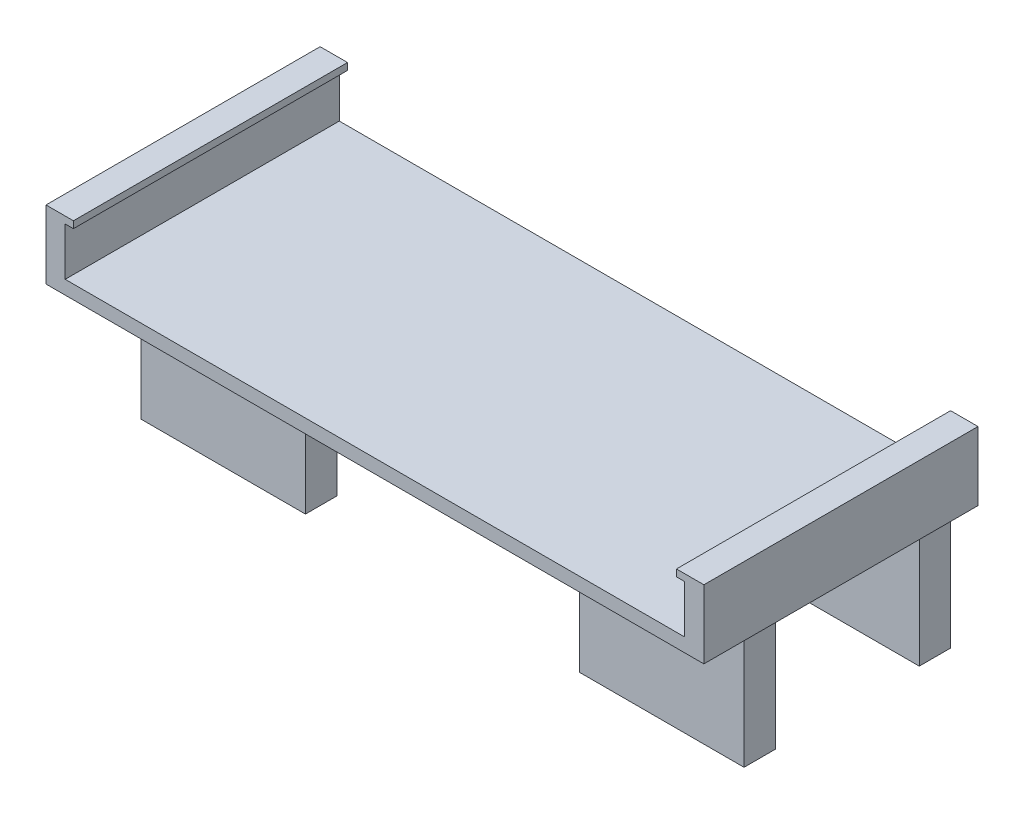
SolidWorks part; units mm, degrees
ref_plane "前视基准面" through (0, 0, 0) normal (0, 0, 1) x (1, 0, 0)
ref_plane "上视基准面" through (0, 0, 0) normal (0, 1, 0) x (1, 0, 0)
ref_plane "右视基准面" through (0, 0, 0) normal (1, 0, 0) x (0, 0, -1)
sketch "草图1" plane through (0, 0, 0) normal (0, 1, 0) x (1, 0, 0)
  line L1 (-24.78, 14.6257) -> (23.22, 14.6257)
  line L2 (-24.78, 14.6257) -> (-24.78, -5.3743)
  line L3 (-24.78, -5.3743) -> (23.22, -5.3743)
  line L4 (23.22, 14.6257) -> (23.22, -5.3743)
  dimension "D1" = 48
  dimension "D2" = 20
extrude "凸台-拉伸1" add sketch "草图1" along normal blind 5
sketch "草图2" plane through (0, 0, 5.3743) normal (0, 0, 1) x (1, 0, 0)
  line L7 (-22.78, 5) -> (-22.78, 4.5)
  line L8 (-24.78, 5) -> (23.22, 5) construction
  line L9 (-22.78, 4.5) -> (-23.38, 4.5)
  line L10 (-23.38, 4.5) -> (-23.38, 1)
  line L11 (-23.38, 1) -> (21.82, 1)
  line L12 (21.82, 1) -> (21.82, 4.5)
  line L13 (21.82, 4.5) -> (21.22, 4.5)
  line L14 (21.22, 4.5) -> (21.22, 5)
  line L15 (21.22, 5) -> (-22.78, 5)
  line L16 (23.22, 5) -> (23.22, 0) construction
  line L17 (-24.78, 5) -> (-24.78, 0) construction
  line L18 (-24.78, 0) -> (23.22, 0) construction
  dimension "D1" = 2
  dimension "D2" = 2
  dimension "D3" = 0.6
  dimension "D4" = 0.6
  dimension "D5" = 0.5
  dimension "D6" = 1
extrude "切除-拉伸1" cut sketch "草图2" against normal through all
sketch "草图3" plane through (0, 0, 0) normal (0, -1, 0) x (1, 0, 0)
  line L6 (-22.78, 0.4443) -> (-22.78, -14.6257)
  line L7 (23.22, -14.6257) -> (-24.78, -14.6257) construction
  line L8 (-22.78, -14.6257) -> (-10.78, -14.6257)
  line L9 (-10.78, -14.6257) -> (-10.78, 0.4443)
  line L10 (-10.78, 0.4443) -> (-22.78, 0.4443)
  line L11 (9.22, 0.4443) -> (9.22, -14.6257)
  line L12 (9.22, -14.6257) -> (21.22, -14.6257)
  line L13 (21.22, -14.6257) -> (21.22, 0.4443)
  line L14 (21.22, 0.4443) -> (9.22, 0.4443)
  line L15 (-24.78, -14.6257) -> (-24.78, 5.3743) construction
  dimension "D1" = 12
  dimension "D2" = 12
  dimension "D3" = 20
  dimension "D4" = 2
  dimension "D5" = 15.07
  dimension "D6" = 15.07
extrude "凸台-拉伸2" add sketch "草图3" along normal blind 10
sketch "草图4" plane through (21.22, 0, 0) normal (1, 0, 0) x (0, 0, -1)
  line L0 (1.8407, -2) -> (1.8407, -10)
  line L1 (14.6257, -10) -> (-0.4443, -10) construction
  line L2 (1.8407, -10) -> (12.3407, -10)
  line L3 (12.3407, -10) -> (12.3407, -2)
  line L4 (12.3407, -2) -> (1.8407, -2)
  line L5 (14.6257, -10) -> (14.6257, 0) construction
  point P8 (14.6257, -5)
  dimension "D1" = 8
  dimension "D2" = 10.5
  dimension "D3" = 2.285
extrude "切除-拉伸2" cut sketch "草图4" against normal through all
